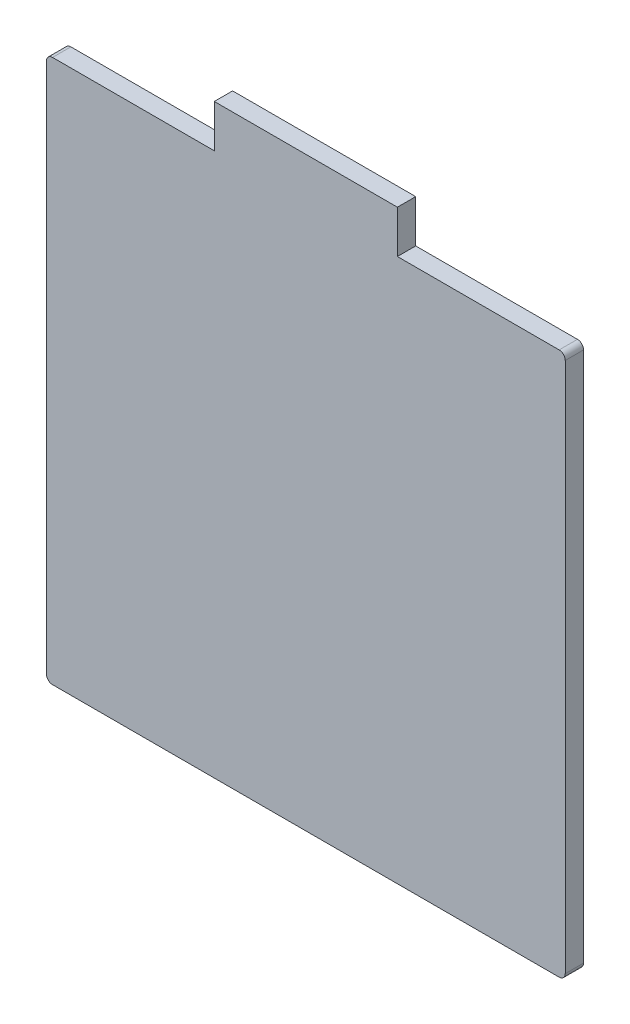
SolidWorks part; units mm, degrees
ref_plane "Front Plane" through (0, 0, 0) normal (1, 0, 0) x (0, 1, 0)
ref_plane "Top Plane" through (0, 0, 0) normal (0, 0, 1) x (0, 1, 0)
ref_plane "Right Plane" through (0, 0, 0) normal (0, 1, 0) x (-1, 0, 0)
sketch "Sketch1" plane through (0, 0, 0) normal (0, 0, 1) x (0, 1, 0)
  line L1 (445, -425) -> (-445, -425)
  line L2 (445, -425) -> (445, 425)
  line L3 (445, 425) -> (-445, 425)
  line L4 (-445, -425) -> (-445, 425)
  line L5 (445, -425) -> (-445, 425) construction
  line L6 (445, 425) -> (-445, -425) construction
  point P0 (0, 0)
  dimension "D1" = 890
  dimension "D2" = 850
extrude "Boss-Extrude1" add sketch "Sketch1" along normal blind 30
fillet "Fillet1" radius 10 4 edges at (-425, -445, 15) (-425, 445, 15) (425, 445, 15) (425, -445, 15)
sketch "Sketch3" plane through (0, 445, 0) normal (0, 1, 0) x (-1, 0, 0)
  line L0 (0, 0) -> (-150, 0)
  line L1 (-415, 0) -> (415, 0) construction
  line L2 (-150, 0) -> (-150, 30)
  line L3 (-415, 30) -> (415, 30) construction
  line L4 (-150, 30) -> (150, 30)
  line L5 (150, 30) -> (150, 0)
  line L6 (150, 0) -> (0, 0)
  dimension "D1" = 300
extrude "Boss-Extrude3" add sketch "Sketch3" along normal blind 70
